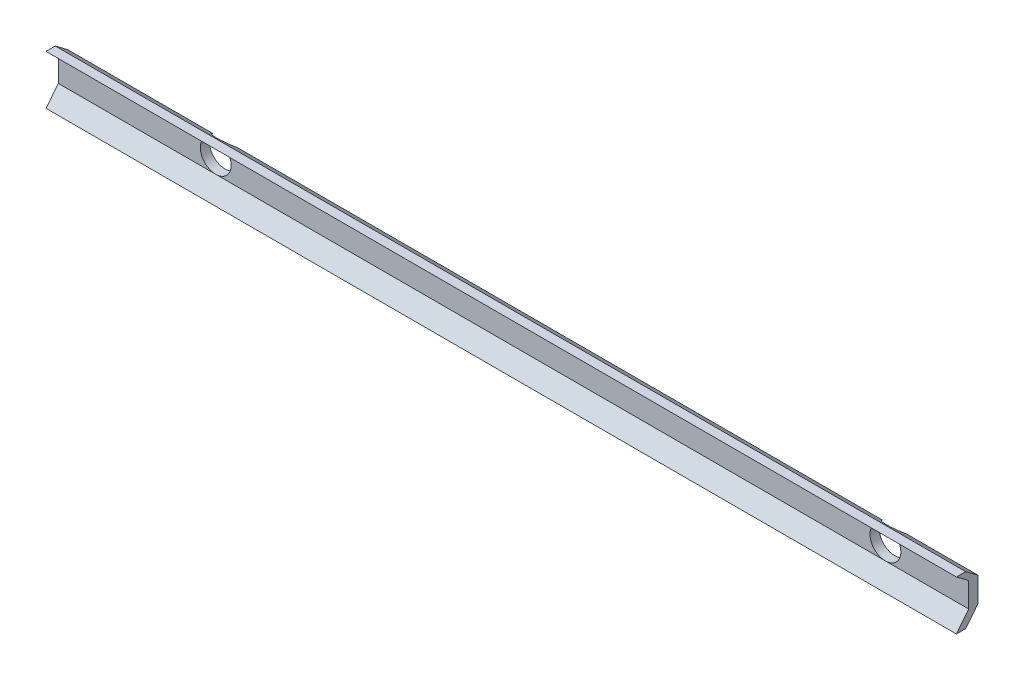
SolidWorks part; units mm, degrees
ref_plane "Front Plane" through (0, 0, 0) normal (0, 0, 1) x (1, 0, 0)
ref_plane "Top Plane" through (0, 0, 0) normal (0, 1, 0) x (1, 0, 0)
ref_plane "Right Plane" through (0, 0, 0) normal (1, 0, 0) x (0, 0, -1)
sketch "Main Body Sketch" plane through (0, 0, 0) normal (1, 0, 0) x (0, 0, -1)
  line L0 (0, 0) -> (2, -1.5)
  line L1 (2, -1.5) -> (2, -5.5)
  line L2 (2, -5.5) -> (0, -8)
  line L3 (0, 0) -> (1.5, 0)
  line L4 (1.5, 0) -> (3.5, -1.5)
  line L5 (3.5, -1.5) -> (3.5, -5.5)
  line L6 (3.5, -5.5) -> (1.5, -8)
  line L7 (0, -8) -> (1.5, -8)
  dimension "D1" = 1.5
  dimension "D2" = 5.5
  dimension "D3" = 2.5
  dimension "D4" = 2
  dimension "D5" = 1.5
extrude "Main Body Extrude" add sketch "Main Body Sketch" against normal blind 147.5
sketch "Cross Bolt Bore Sketch" plane through (0, 0, -3.5) normal (0, 0, -1) x (-1, 0, 0)
  line L0 (147.5, 0) -> (0, 0) construction
  line L4 (0, -5.5) -> (0, -1.5) construction
  circle A0 centre (13.5, -3) radius 2.5
  circle A1 centre (122, -3) radius 2.5
  dimension "D1" = 5
  dimension "D4" = 5
  dimension "D5" = 3
  dimension "D2" = 3
  dimension "D3" = 13.5
  dimension "D6" = 108.5
extrude "Cross Bolt Bore Extrude" cut sketch "Cross Bolt Bore Sketch" against normal through all
